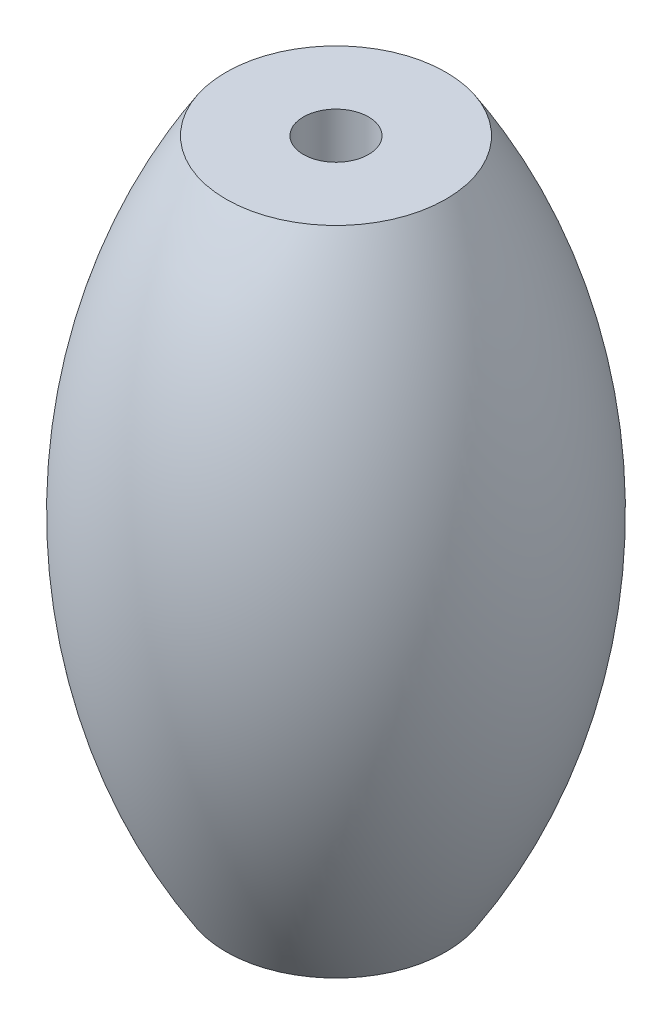
SolidWorks part; units mm, degrees
ref_plane "Front" through (0, 0, 0) normal (0, 0, 1) x (1, 0, 0)
ref_plane "Top" through (0, 0, 0) normal (0, 1, 0) x (1, 0, 0)
ref_plane "Right" through (0, 0, 0) normal (1, 0, 0) x (0, 0, -1)
sketch "Sketch1" plane through (0, 0, 0) normal (0, 0, 1) x (1, 0, 0)
  line L0 (-3.7, 7.5) -> (3.7, 7.5)
  line L1 (-3.7, -7.5) -> (3.7, -7.5)
  line L2 (9.2904, 0) -> (-3.7, 7.5) construction
  line L3 (9.2904, 0) -> (-3.7, -7.5) construction
  line L4 (-0.75, 7.5) -> (-0.75, -7.5)
  line L5 (0.75, 7.5) -> (0.75, -7.5)
  line L6 (-0.75, 0) -> (0, 0) construction
  line L7 (0, 0) -> (0.75, 0) construction
  line L8 (0, -10.7218) -> (0, 16.5219) construction
  arc A0 (-3.7, 7.5) -> (-3.7, -7.5) centre (9.2904, 0) ccw
  arc A1 (3.7, 7.5) -> (3.7, -7.5) centre (-9.2904, 0) cw
  arc A2 (-2.5312, 7.5) -> (-2.5312, -7.5) centre (9.2904, 0) ccw
  arc A3 (2.5312, 7.5) -> (2.5312, -7.5) centre (-9.2904, 0) cw
  point P2 (0, 7.5)
  dimension "D2" = 15
  dimension "D3" = 1
  dimension "D6" = 1
  dimension "D1" = 7.4
  dimension "D4" = 60
  dimension "D5" = 1.5
revolve "Revolve1" add sketch "Sketch1" angle 360 about L8
